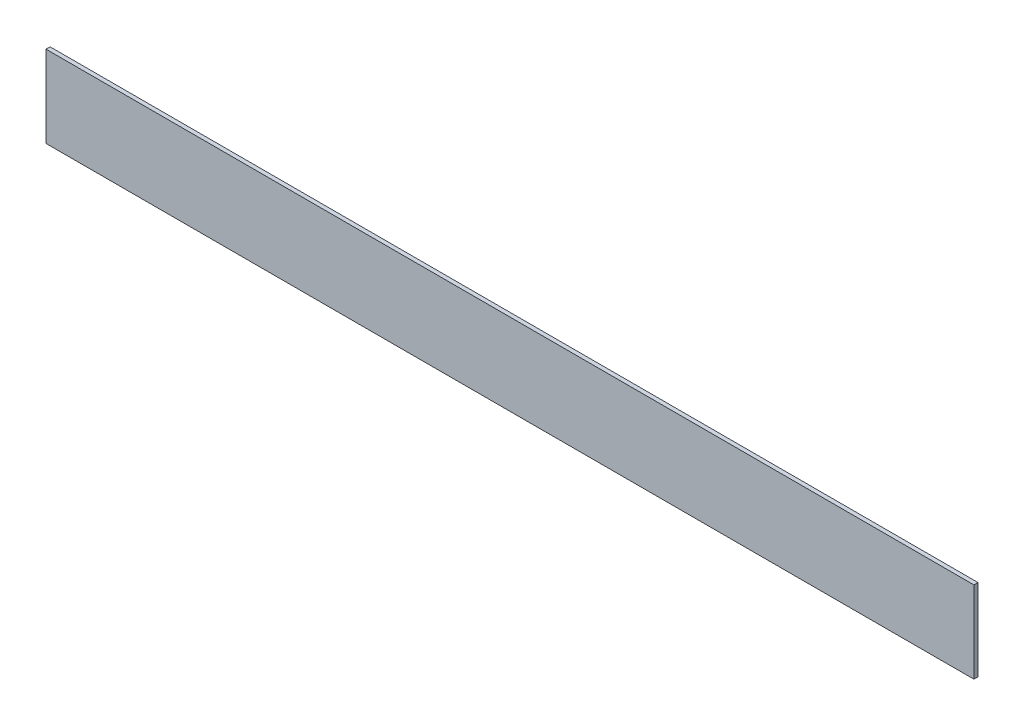
SolidWorks part; units mm, degrees
ref_plane "Plano frontal" through (0, 0, 0) normal (0, 0, 1) x (1, 0, 0)
ref_plane "Plano superior" through (0, 0, 0) normal (0, 1, 0) x (1, 0, 0)
ref_plane "Plano direito" through (0, 0, 0) normal (1, 0, 0) x (0, 0, -1)
sketch "Sketch1" plane through (0, 0, 0) normal (0, 0, 1) x (1, 0, 0)
  line L1 (1135.875, 100) -> (-1135.875, 100)
  line L2 (1135.875, 100) -> (1135.875, -100)
  line L3 (1135.875, -100) -> (-1135.875, -100)
  line L4 (-1135.875, 100) -> (-1135.875, -100)
  line L5 (1135.875, 100) -> (-1135.875, -100) construction
  line L6 (1135.875, -100) -> (-1135.875, 100) construction
  point P0 (0, 0)
extrude "Boss-Extrude1" add sketch "Sketch1" along normal blind 10
